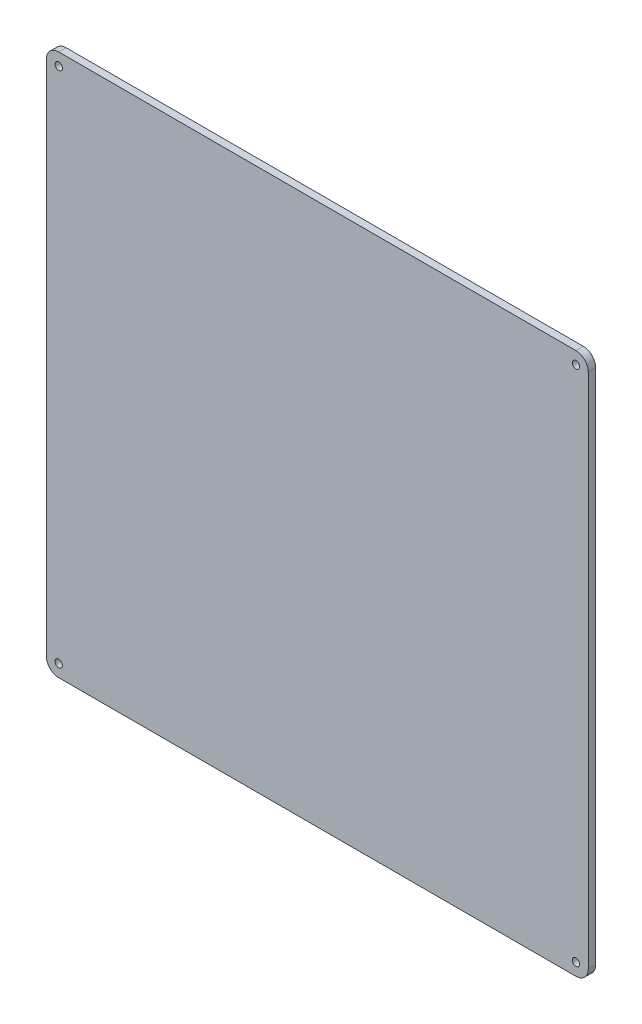
SolidWorks part; units mm, degrees
ref_plane "Płaszczyzna przednia" through (0, 0, 0) normal (0, 0, 1) x (1, 0, 0)
ref_plane "Płaszczyzna górna" through (0, 0, 0) normal (0, 1, 0) x (1, 0, 0)
ref_plane "Płaszczyzna prawa" through (0, 0, 0) normal (1, 0, 0) x (0, 0, -1)
sketch "Szkic1" plane through (0, 0, 0) normal (0, 0, 1) x (1, 0, 0)
  line L1 (-110, -110) -> (110, -110)
  line L2 (-110, -110) -> (-110, 110)
  line L3 (-110, 110) -> (110, 110)
  line L4 (110, -110) -> (110, 110)
  line L5 (-110, -110) -> (110, 110) construction
  line L6 (-110, 110) -> (110, -110) construction
  point P0 (0, 0)
  dimension "D1" = 220
  dimension "D2" = 220
extrude "Dodanie-wyciągnięcie1" add sketch "Szkic1" along normal blind 3
sketch "Szkic2" plane through (0, 0, 0) normal (0, 0, -1) x (-1, 0, 0)
  circle A0 centre (105, -105) radius 1.5
  circle A1 centre (105, 105) radius 1.5
  circle A2 centre (-105, 105) radius 1.5
  circle A3 centre (-105, -105) radius 1.5
  dimension "D1" = 3
  dimension "D2" = 3
  dimension "D3" = 3
  dimension "D4" = 3
extrude "Wytnij-wyciągnięcie2" cut sketch "Szkic2" against normal up to next
fillet "Zaokrąglenie1" radius 5 4 edges at (110, -110, 1.5) (110, 110, 1.5) (-110, 110, 1.5) (-110, -110, 1.5)
